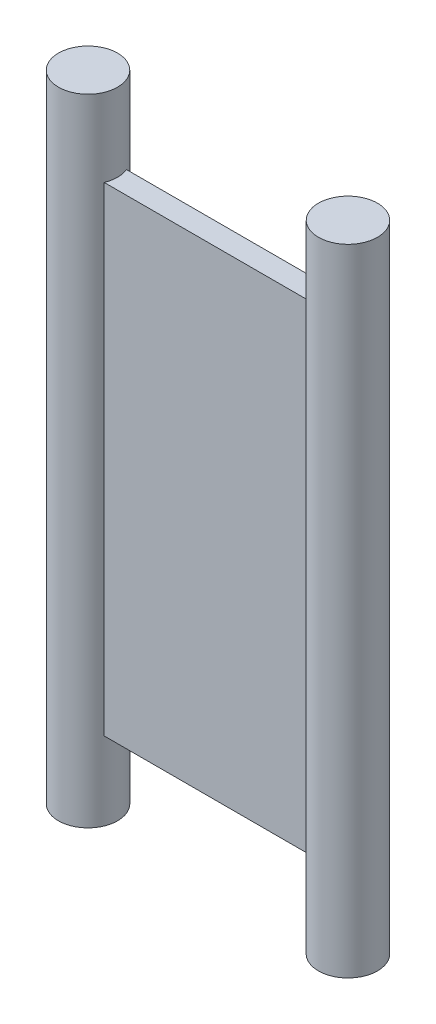
SolidWorks part; units mm, degrees
ref_plane "Front Plane" through (0, 0, 0) normal (0, 0, 1) x (1, 0, 0)
ref_plane "Top Plane" through (0, 0, 0) normal (0, 1, 0) x (1, 0, 0)
ref_plane "Right Plane" through (0, 0, 0) normal (1, 0, 0) x (0, 0, -1)
sketch "Sketch1" plane through (0, 0, 0) normal (0, 1, 0) x (1, 0, 0)
  line L1 (5.83, 0.5) -> (-5.83, 0.5)
  line L2 (5.83, 0.5) -> (5.83, -0.5)
  line L3 (5.83, -0.5) -> (-5.83, -0.5)
  line L4 (-5.83, 0.5) -> (-5.83, -0.5)
  line L5 (5.83, 0.5) -> (-5.83, -0.5) construction
  line L6 (5.83, -0.5) -> (-5.83, 0.5) construction
  point P0 (0, 0)
  dimension "D1" = 11.66
  dimension "D3" = 1
extrude "Boss-Extrude1" add sketch "Sketch1" along normal blind 21.5
ref_plane "Plane1" through (0, 10.75, 0) normal (0, 1, 0) x (1, 0, 0)
sketch "Sketch2" plane through (0, 10.75, 0) normal (0, 1, 0) x (1, 0, 0)
  line L0 (5.83, -0.5) -> (5.83, 0.5) construction
  line L1 (-5.83, 0.5) -> (-5.83, -0.5) construction
  line L2 (5.83, -0.5) -> (5.83, 0.5) construction
  line L3 (-5.83, 0.5) -> (-5.83, -0.5) construction
  circle A0 centre (-5.83, 0) radius 1.325
  circle A1 centre (5.83, 0) radius 1.325
  dimension "D1" = 2.65
extrude "Boss-Extrude2" add sketch "Sketch2" along normal mid plane 28.5
